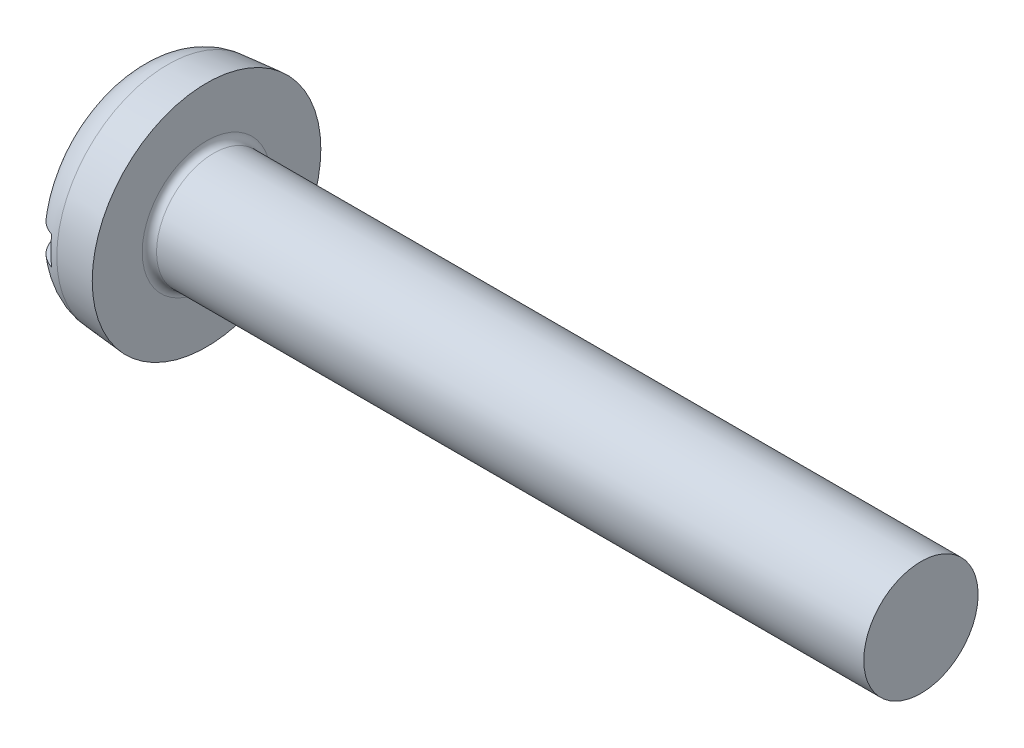
SolidWorks part; units mm, degrees
ref_plane "Front Plane" through (0, 0, 0) normal (0, 0, 1) x (1, 0, 0)
ref_plane "Top Plane" through (0, 0, 0) normal (0, 1, 0) x (1, 0, 0)
ref_plane "Right Plane" through (0, 0, 0) normal (1, 0, 0) x (0, 0, -1)
sketch "BodySke" plane through (0, 0, 0) normal (0, 0, 1) x (1, 0, 0)
  line L0 (0, 0) -> (19.6365, 0) construction
  line L1 (0, 0) -> (0, 1.5125)
  line L2 (0, 1.5125) -> (1, 1.6)
  line L3 (1, 1.6) -> (1, 0.8)
  line L4 (1, 0.8) -> (11, 0.8)
  line L5 (11, 0.8) -> (11, 0)
  line L6 (11, 0) -> (0, 0)
  line L7 (10.65, 0) -> (10.65, 0.8) construction
  line L8 (1, 0) -> (1, 0.8) construction
  point P12 (11, 0.601)
  dimension "Thread_minor" = 3.22
  dimension "Head_side_angle" = 5
revolve "BaseBody" add sketch "BodySke" angle 360 about L0
cosmetic thread "ThreadCosmetic" [suppressed] parameters "Thread_length"=16, "Thread_minor"=3.22
fillet "Fillet1" radius 0.1 1 edges at (1, 0, 0.8)
fillet "Head_Radius" radius 0.5 1 edges at (0, 0, 1.5125)
sketch "SlotSke" plane through (0, 0, 0) normal (1, 0, 0) x (0, 0, -1)
  line L0 (-1.6, 0.2) -> (1.6, -0.2) construction
  line L1 (-1.6, 0.2) -> (1.6, 0.2)
  line L2 (-1.6, 0.2) -> (-1.6, -0.2)
  line L3 (-1.6, -0.2) -> (1.6, -0.2)
  line L4 (1.6, 0.2) -> (1.6, -0.2)
  dimension "D1" = 8
extrude "Slot" cut sketch "SlotSke" along normal blind 0.35
sketch "ThdSchSke" plane through (0, 0, 0) normal (0, 0, 1) x (1, 0, 0)
  line L0 (10.8851, 1.0298) -> (10.8851, 0.8)
  line L1 (10.8851, 1.0298) -> (11.1149, 1.0298)
  line L2 (11.1149, 1.0298) -> (11.1149, 0.8)
  line L3 (11.1149, 0.8) -> (11, 0.601)
  line L4 (11, 0.601) -> (10.8851, 0.8)
  line L5 (1, 0.8) -> (11, 0.8) construction
  line L6 (0, 0) -> (12.5247, 0) construction
  line L7 (0, 0) -> (19.6365, 0) construction
revolve "ThreadSchematic" [suppressed] cut sketch "ThdSchSke" angle 360 about L6
pattern_linear "ThdSchPat" [suppressed]
equation "\"Thread_minor@ThreadCosmetic\" = \"Thread_minor@BodySke\""
equation "\"Thread_length@ThreadCosmetic\" = \"Thread_length@BodySke\""
equation "\"D1@SlotSke\" = \"Head_diameter@BodySke\""
equation "\"Advance@ThdSchPat\" = \"Advance@BodySke\""
equation "\"Tooth_Num@ThdSchPat\" =  int( \"Thread_length@BodySke\" / \"Advance@BodySke\" ) "
